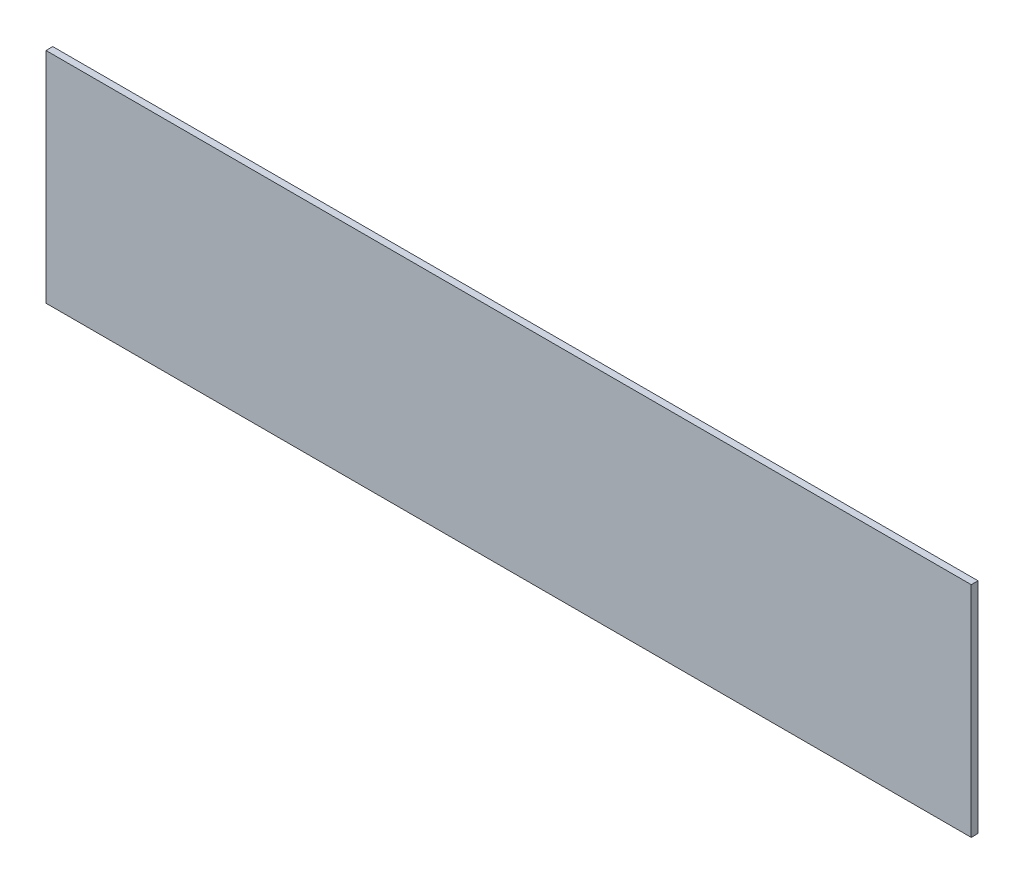
SolidWorks part; units mm, degrees
ref_plane "Alzado" through (0, 0, 0) normal (0, 0, 1) x (1, 0, 0)
ref_plane "Planta" through (0, 0, 0) normal (0, 1, 0) x (1, 0, 0)
ref_plane "Vista lateral" through (0, 0, 0) normal (1, 0, 0) x (0, 0, -1)
sketch "Croquis1" plane through (0, 0, 0) normal (0, 0, 1) x (1, 0, 0)
  line L1 (-205, 48.5) -> (205, 48.5)
  line L2 (-205, 48.5) -> (-205, -48.5)
  line L3 (-205, -48.5) -> (205, -48.5)
  line L4 (205, 48.5) -> (205, -48.5)
  line L5 (-205, 48.5) -> (205, -48.5) construction
  line L6 (-205, -48.5) -> (205, 48.5) construction
  point P0 (0, 0)
  dimension "D1" = 97
  dimension "D2" = 410
extrude "Saliente-Extruir1" add sketch "Croquis1" along normal blind 3
